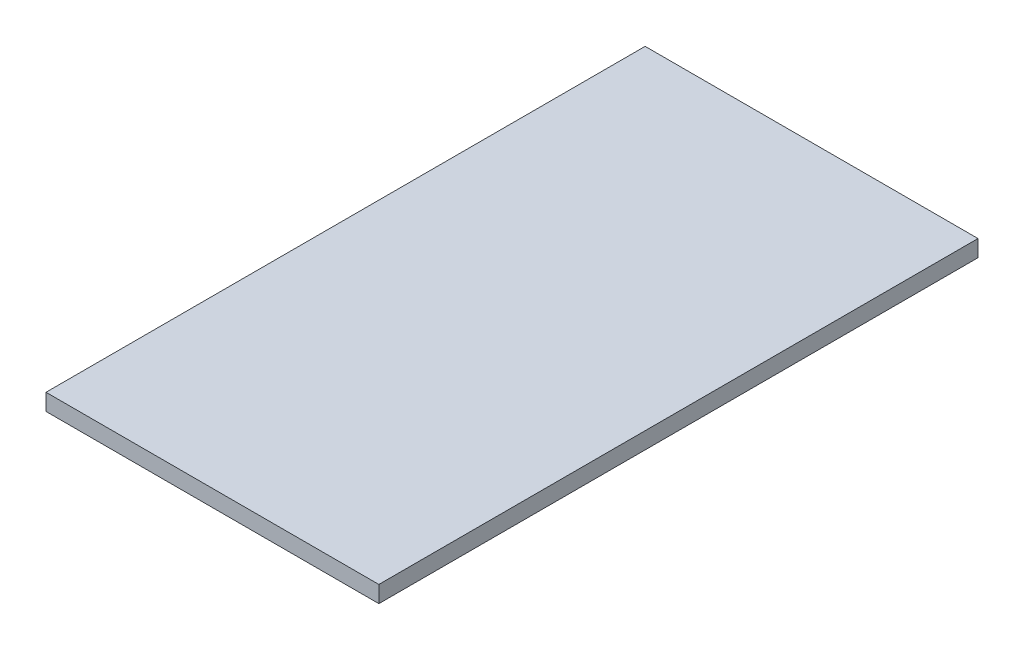
SolidWorks part; units mm, degrees
ref_plane "Front Plane" through (0, 0, 0) normal (0, 0, 1) x (1, 0, 0)
ref_plane "Top Plane" through (0, 0, 0) normal (0, 1, 0) x (1, 0, 0)
ref_plane "Right Plane" through (0, 0, 0) normal (1, 0, 0) x (0, 0, -1)
sketch "Sketch2" plane through (0, 0, 0) normal (0, 1, 0) x (1, 0, 0)
  line L1 (0, 0) -> (127, 0)
  line L2 (0, 0) -> (0, 228.6)
  line L3 (0, 228.6) -> (127, 228.6)
  line L4 (127, 0) -> (127, 228.6)
  dimension "D1" = 127
  dimension "D2" = 228.6
extrude "Boss-Extrude1" add sketch "Sketch2" along normal blind 6.35
